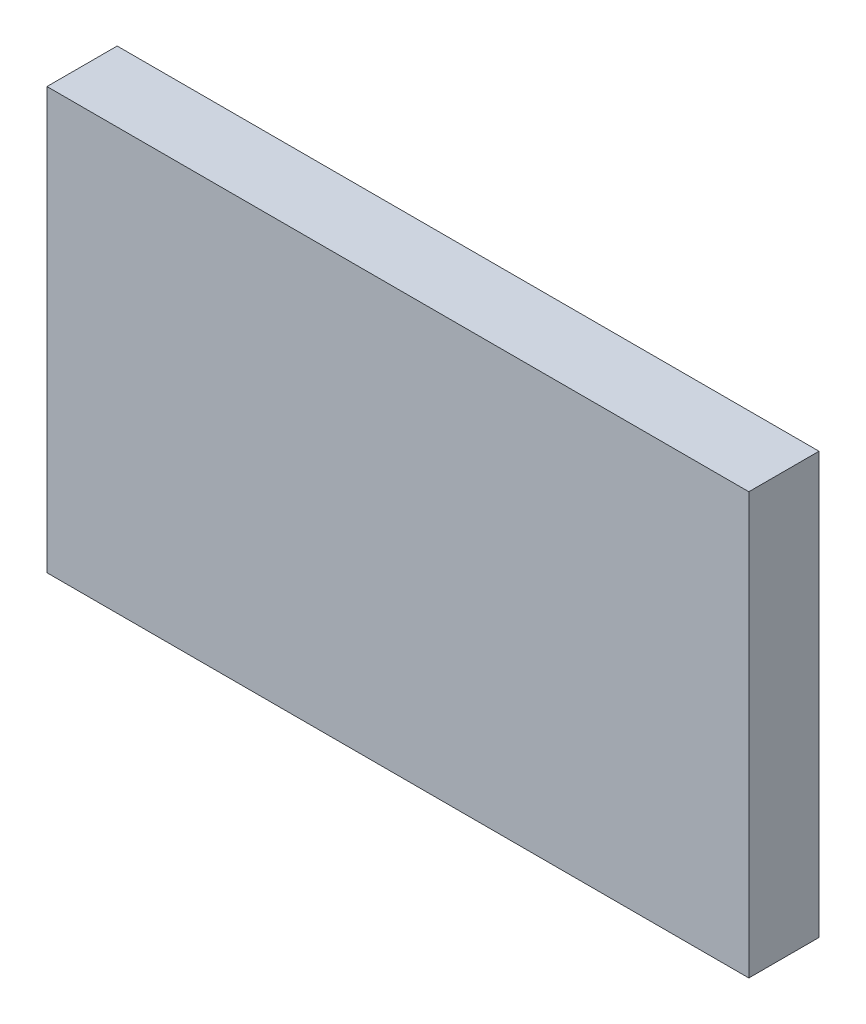
SolidWorks part; units mm, degrees
ref_plane "Front Plane" through (0, 0, 0) normal (0, 0, 1) x (1, 0, 0)
ref_plane "Top Plane" through (0, 0, 0) normal (0, 1, 0) x (1, 0, 0)
ref_plane "Right Plane" through (0, 0, 0) normal (1, 0, 0) x (0, 0, -1)
sketch "Sketch1" plane through (0, 0, 0) normal (0, 0, 1) x (1, 0, 0)
  line L1 (-25, 15) -> (25, 15)
  line L2 (-25, 15) -> (-25, -15)
  line L3 (-25, -15) -> (25, -15)
  line L4 (25, 15) -> (25, -15)
  line L5 (-25, 15) -> (25, -15) construction
  line L6 (-25, -15) -> (25, 15) construction
  point P0 (0, 0)
  dimension "D1" = 50
  dimension "D2" = 30
extrude "Boss-Extrude1" add sketch "Sketch1" along normal blind 5
